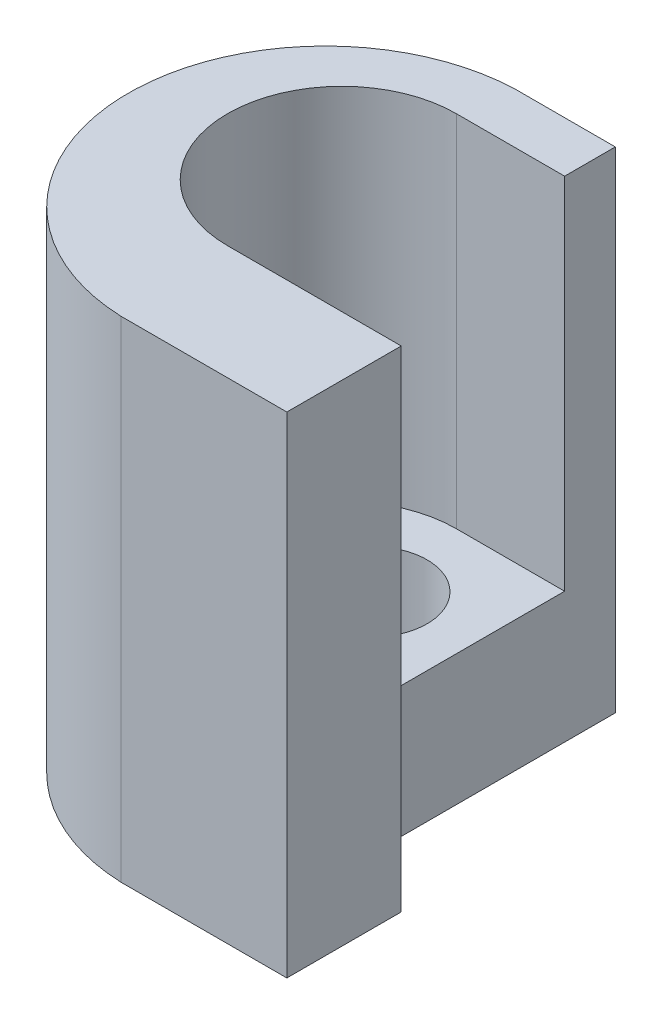
SolidWorks part; units mm, degrees
ref_plane "Front Plane" through (0, 0, 0) normal (0, 0, 1) x (1, 0, 0)
ref_plane "Top Plane" through (0, 0, 0) normal (0, 1, 0) x (1, 0, 0)
ref_plane "Right Plane" through (0, 0, 0) normal (1, 0, 0) x (0, 0, -1)
sketch "Sketch1" plane through (0, 0, 0) normal (0, 1, 0) x (1, 0, 0)
  line L7 (-11.0235, 2.9666) -> (-11.0235, -4.0334)
  line L8 (-11.0235, -4.0334) -> (-14.3382, -4.0334)
  line L9 (-14.3382, 2.9666) -> (-11.0235, 2.9666)
  arc A5 (-14.3382, -4.0334) -> (-14.3382, 2.9666) centre (-14.3382, -0.5334) cw
  circle A6 centre (-13.9635, -0.0034) radius 1.7
  dimension "D6" = 2.94
  dimension "D7" = 2.97
  dimension "D8" = 3.4
  dimension "D5" = 7
extrude "Boss-Extrude2" add sketch "Sketch1" along normal blind 4
sketch "Sketch2" plane through (0, 0, 0) normal (0, 1, 0) x (1, 0, 0)
  line L17 (-11.0235, 2.9666) -> (-11.0235, 4.5176)
  line L18 (-11.0235, 4.5176) -> (-14.1035, 4.5176)
  line L19 (-11.0235, -4.0334) -> (-9.0235, -4.0334)
  line L20 (-9.0235, -4.0334) -> (-9.0235, -7.5334)
  line L21 (-9.0235, -7.5334) -> (-14.1035, -7.5334)
  line L23 (-11.0235, 2.9666) -> (-14.3382, 2.9666)
  line L24 (-14.3382, -4.0334) -> (-11.0235, -4.0334)
  arc A2 (-14.1035, 4.5176) -> (-14.1035, -7.5334) centre (-13.8697, -1.5079) ccw
  arc A3 (-14.3382, 2.9666) -> (-14.3382, -4.0334) centre (-14.3382, -0.5334) ccw
  dimension "D14" = 6.03
  dimension "D9" = 5.08
  dimension "D10" = 2
  dimension "D11" = 3.5
  dimension "D12" = 1.5509
  dimension "D13" = 3.08
extrude "Boss-Extrude3" add sketch "Sketch2" along normal blind 15
